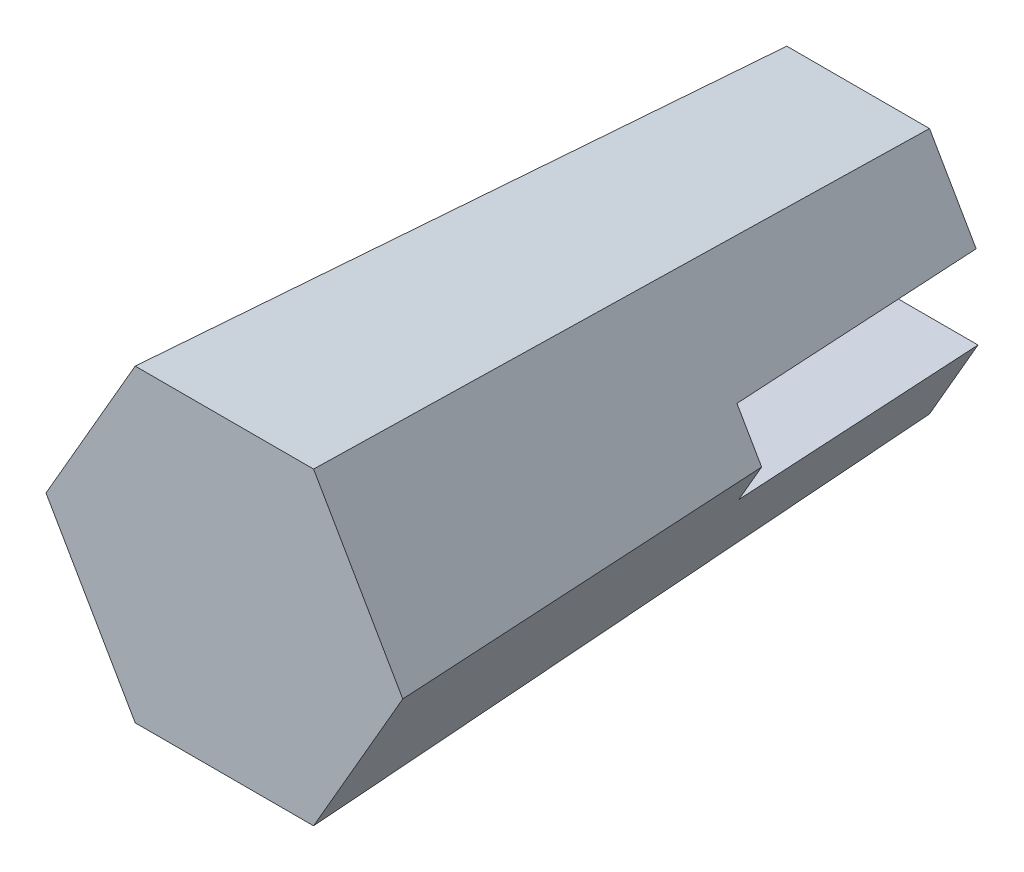
SolidWorks part; units mm, degrees
ref_plane "Front Plane" through (0, 0, 0) normal (0, 0, 1) x (1, 0, 0)
ref_plane "Top Plane" through (0, 0, 0) normal (0, 1, 0) x (1, 0, 0)
ref_plane "Right Plane" through (0, 0, 0) normal (1, 0, 0) x (0, 0, -1)
sketch "Sketch1" plane through (0, 0, 0) normal (0, 0, 1) x (1, 0, 0)
  line L1 (11.4385, 0) -> (5.7192, 9.906)
  line L2 (5.7192, 9.906) -> (-5.7192, 9.906)
  line L3 (-5.7192, 9.906) -> (-11.4385, 0)
  line L4 (-11.4385, 0) -> (-5.7192, -9.906)
  line L5 (-5.7192, -9.906) -> (5.7192, -9.906)
  line L6 (5.7192, -9.906) -> (11.4385, 0)
  circle A0 centre (0, 0) radius 9.906 construction
  dimension "D1" = 19.812
ref_plane "Plane4" through (0, 0, 50.8) normal (0, 0, 1) x (1, 0, 0)
sketch "Sketch2" plane through (0, 0, 50.8) normal (0, 0, 1) x (1, 0, 0)
  line L6 (-14.2981, 0) -> (-7.149, -12.3825)
  line L7 (-7.149, -12.3825) -> (7.149, -12.3825)
  line L8 (7.149, -12.3825) -> (14.2981, 0)
  line L9 (14.2981, 0) -> (7.149, 12.3825)
  line L10 (-7.149, 12.3825) -> (-14.2981, 0)
  line L11 (7.149, 12.3825) -> (-7.149, 12.3825)
loft "Loft1" add profiles "Sketch2", "Sketch1"
sketch "Sketch4" plane through (0, 0, 0) normal (0, 0, -1) x (-1, 0, 0)
  line L0 (-9.4587, 3.429) -> (9.4587, 3.429)
  line L1 (-11.4385, 0) -> (-5.7192, 9.906) construction
  line L2 (5.7192, 9.906) -> (11.4385, 0) construction
  line L4 (11.4385, 0) -> (5.7192, -9.906) construction
  line L5 (9.6054, -3.175) -> (-9.6054, -3.175)
  line L6 (-5.7192, -9.906) -> (-11.4385, 0) construction
  line L8 (-9.4587, 3.429) -> (-15.6932, 3.429)
  line L9 (-15.6932, 3.429) -> (-15.6932, -3.175)
  line L10 (-15.6932, -3.175) -> (-9.6054, -3.175)
  line L11 (9.6054, -3.175) -> (15.6932, -3.175)
  line L12 (15.6932, -3.175) -> (15.6932, 3.429)
  line L13 (15.6932, 3.429) -> (9.4587, 3.429)
  dimension "D1" = 6.604
extrude "Cut-Extrude1" cut sketch "Sketch4" against normal blind 20.32
